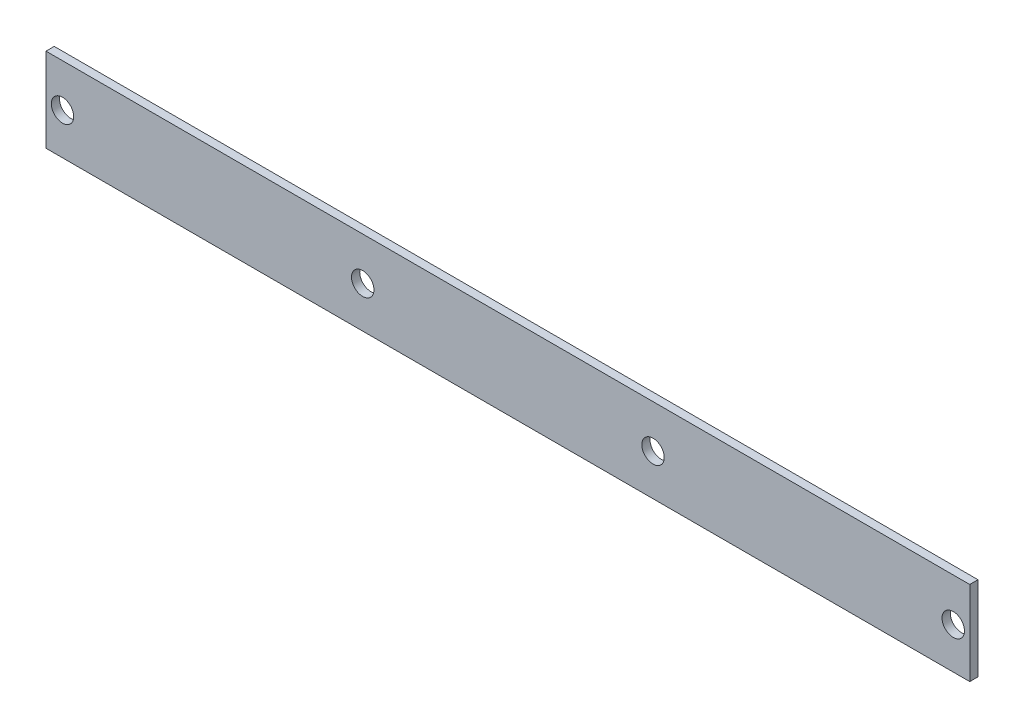
SolidWorks part; units mm, degrees
ref_plane "Front Plane" through (0, 0, 0) normal (0, 0, 1) x (1, 0, 0)
ref_plane "Top Plane" through (0, 0, 0) normal (0, 1, 0) x (1, 0, 0)
ref_plane "Right Plane" through (0, 0, 0) normal (1, 0, 0) x (0, 0, -1)
sketch "Sketch1" plane through (0, 0, 0) normal (0, 0, 1) x (1, 0, 0)
  line L0 (0, 9.1475) -> (0, -5.266) construction
  line L1 (-140, 13) -> (140, 13)
  line L2 (-140, 13) -> (-140, -12.5)
  line L3 (-140, -12.5) -> (140, -12.5)
  line L4 (140, 13) -> (140, -12.5)
  circle A0 centre (135, 0) radius 3.4
  circle A1 centre (44, 0) radius 3.4
  circle A2 centre (-135, 0) radius 3.4
  circle A3 centre (-44, 0) radius 3.4
  dimension "D1" = 6.8
  dimension "D2" = 2
extrude "Boss-Extrude1" add sketch "Sketch1" along normal blind 2.5
